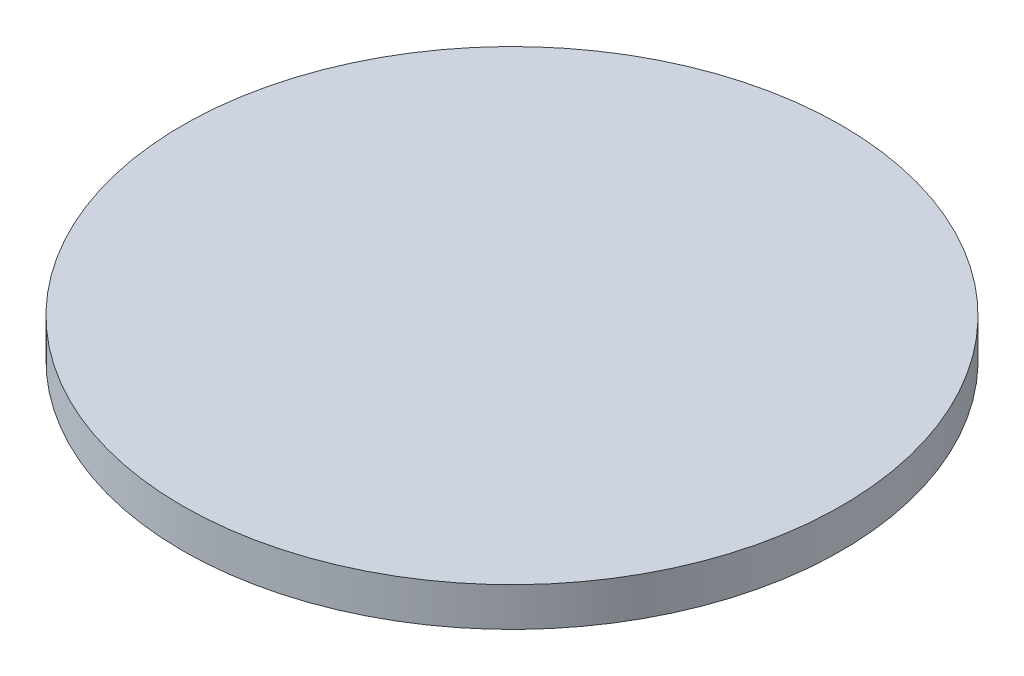
SolidWorks part; units mm, degrees
ref_plane "Front Plane" through (0, 0, 0) normal (0, 0, 1) x (1, 0, 0)
ref_plane "Top Plane" through (0, 0, 0) normal (0, 1, 0) x (1, 0, 0)
ref_plane "Right Plane" through (0, 0, 0) normal (1, 0, 0) x (0, 0, -1)
other "Configuration Table"
sketch "Sketch1" plane through (0, 0, 0) normal (0, 1, 0) x (1, 0, 0)
  circle A0 centre (350, 280) radius 170
extrude "PRESS_PZP400_alt_plaka_D340" add sketch "Sketch1" along normal blind 20 from offset 890 separate body
